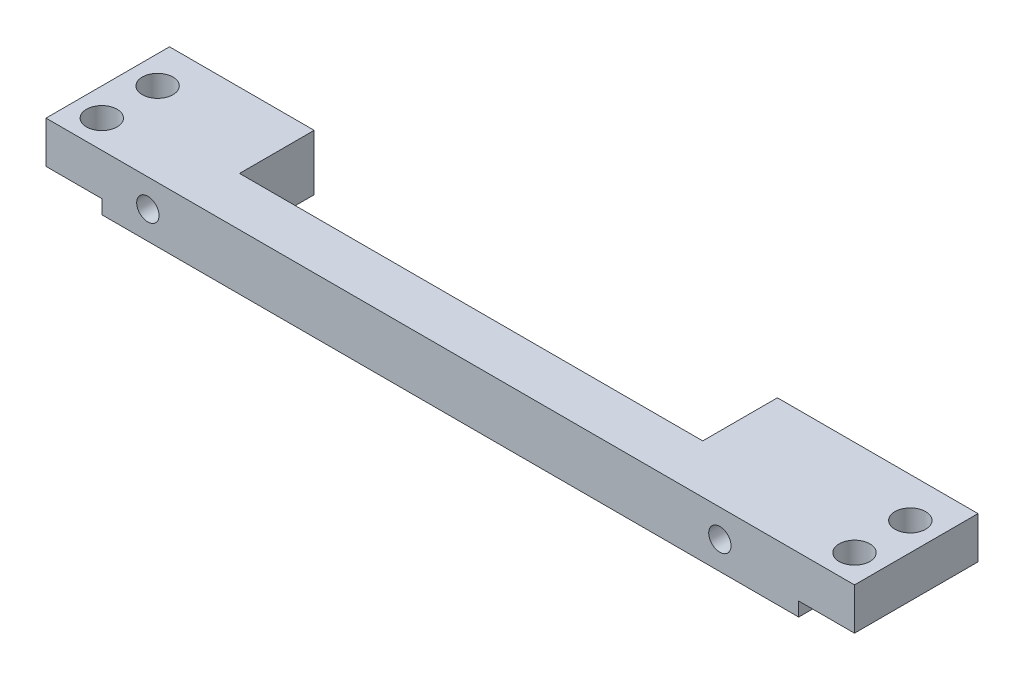
SolidWorks part; units mm, degrees
material "6061-T6 (SS)"
ref_plane "前视基准面" through (0, 0, 0) normal (0, 0, 1) x (1, 0, 0)
ref_plane "上视基准面" through (0, 0, 0) normal (0, 1, 0) x (1, 0, 0)
ref_plane "右视基准面" through (0, 0, 0) normal (1, 0, 0) x (0, 0, -1)
other "Configuration Table"
sketch "草图1" plane through (0, 0, 0) normal (0, 0, 1) x (1, 0, 0)
  line L1 (-4.3, 41.68) -> (53.65, 41.68)
  line L2 (-4.3, 41.68) -> (-4.3, 45.68)
  line L3 (-4.3, 45.68) -> (53.65, 45.68)
  line L4 (53.65, 41.68) -> (53.65, 45.68)
  dimension "D1" = 53.65
  dimension "D2" = 4.3
  dimension "D3" = 41.68
  dimension "D4" = 45.68
extrude "Main_Stock" add sketch "草图1" along normal blind 8.8519 from offset 2.2481
sketch "草图2" plane through (0, 0, 11.1) normal (0, 0, 1) x (1, 0, 0)
  line L1 (-4.3, 41.68) -> (-0.3, 41.68)
  line L2 (-4.3, 41.68) -> (-4.3, 42.68)
  line L3 (-4.3, 42.68) -> (-0.3, 42.68)
  line L4 (-0.3, 41.68) -> (-0.3, 42.68)
  dimension "D1" = 0.3
  dimension "D2" = 4.3
  dimension "D3" = 41.68
  dimension "D4" = 42.68
extrude "Corner_Left_Rectangular_Notch_4x1" cut sketch "草图2" against normal blind 8.8519
sketch "草图3" plane through (0, 0, 11.1) normal (0, 0, 1) x (1, 0, 0)
  line L1 (49.65, 41.68) -> (53.65, 41.68)
  line L2 (49.65, 41.68) -> (49.65, 42.68)
  line L3 (49.65, 42.68) -> (53.65, 42.68)
  line L4 (53.65, 41.68) -> (53.65, 42.68)
  dimension "D1" = 49.65
  dimension "D2" = 53.65
  dimension "D3" = 41.68
  dimension "D4" = 42.68
extrude "Corner_Right_Rectangular_Notch_4x1" cut sketch "草图3" against normal blind 8.8519
sketch "草图4" plane through (0, 0, 11.1) normal (0, 0, 1) x (1, 0, 0)
  circle A0 centre (3, 43.68) radius 0.8
  circle A1 centre (44, 43.68) radius 0.8
  dimension "D1" = 1.6
  dimension "D2" = 3
  dimension "D3" = 44
  dimension "D4" = 43.68
extrude "Frame_2xD1p6_Through" cut sketch "草图4" against normal through all
cosmetic thread "Frame_M2_Through_Cosmetic_1" parameters "D2"=2
cosmetic thread "Frame_M2_Through_Cosmetic_2" parameters "D2"=2
sketch "草图5" plane through (0, 45.68, 0) normal (0, 1, 0) x (1, 0, 0)
  line L1 (6.07, -0.9) -> (39.273, -0.9)
  line L2 (6.07, -0.9) -> (6.07, -7.6)
  line L3 (6.07, -7.6) -> (39.273, -7.6)
  line L4 (39.273, -0.9) -> (39.273, -7.6)
  dimension "D1" = 6.07
  dimension "D2" = 39.273
  dimension "D3" = 0.9
  dimension "D4" = 7.6
extrude "Merged_Interface_Window_33p203x6p7" cut sketch "草图5" against normal blind 4
sketch "草图6" plane through (0, 45.68, 0) normal (0, 1, 0) x (1, 0, 0)
  circle A0 centre (-2.3, -5.1) radius 1.1
  circle A1 centre (-2.3, -9.1) radius 1.1
  circle A2 centre (51.65, -5.1) radius 1.1
  circle A3 centre (51.65, -9.1) radius 1.1
  dimension "D1" = 2.2
  dimension "D2" = 51.65
  dimension "D3" = 2.3
  dimension "D4" = 5.1
  dimension "D5" = 9.1
extrude "Corner_Rear_4xD2p2_Through" cut sketch "草图6" against normal through all
